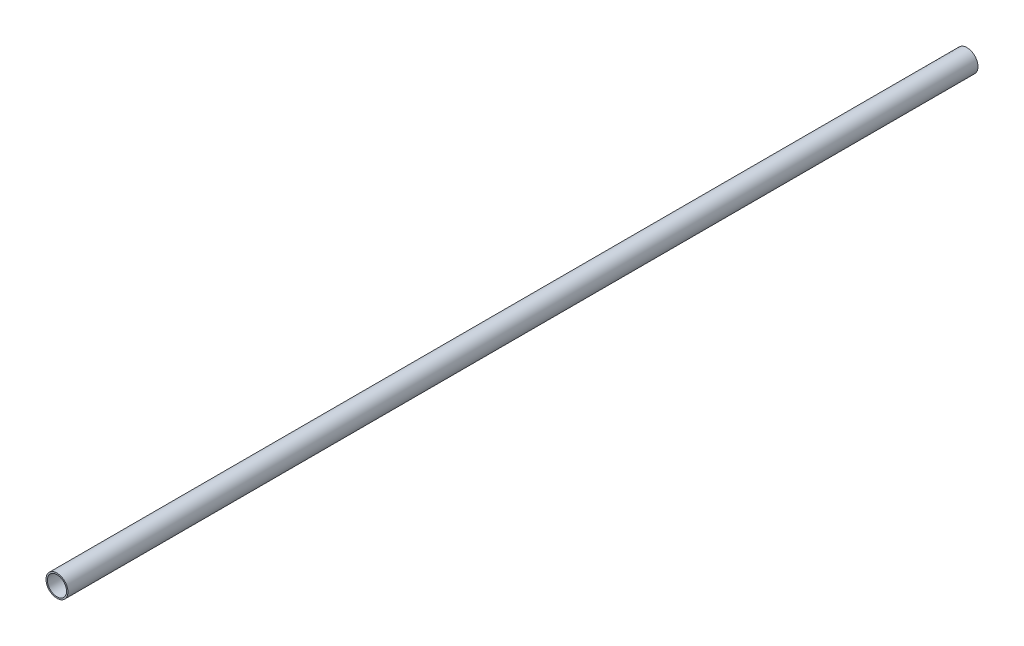
SolidWorks part; units mm, degrees
ref_plane "Plano frontal" through (0, 0, 0) normal (0, 0, 1) x (1, 0, 0)
ref_plane "Plano superior" through (0, 0, 0) normal (0, 1, 0) x (1, 0, 0)
ref_plane "Plano direito" through (0, 0, 0) normal (1, 0, 0) x (0, 0, -1)
sketch "Sketch2" plane through (0, 0, 0) normal (0, 0, 1) x (1, 0, 0)
  circle A0 centre (2449.7201, -5187.0074) radius 24.125
  circle A1 centre (2449.7201, -5187.0074) radius 21.075
  dimension "D1" = 3.05
extrude "Boss-Extrude1" add sketch "Sketch2" along normal blind 2000
